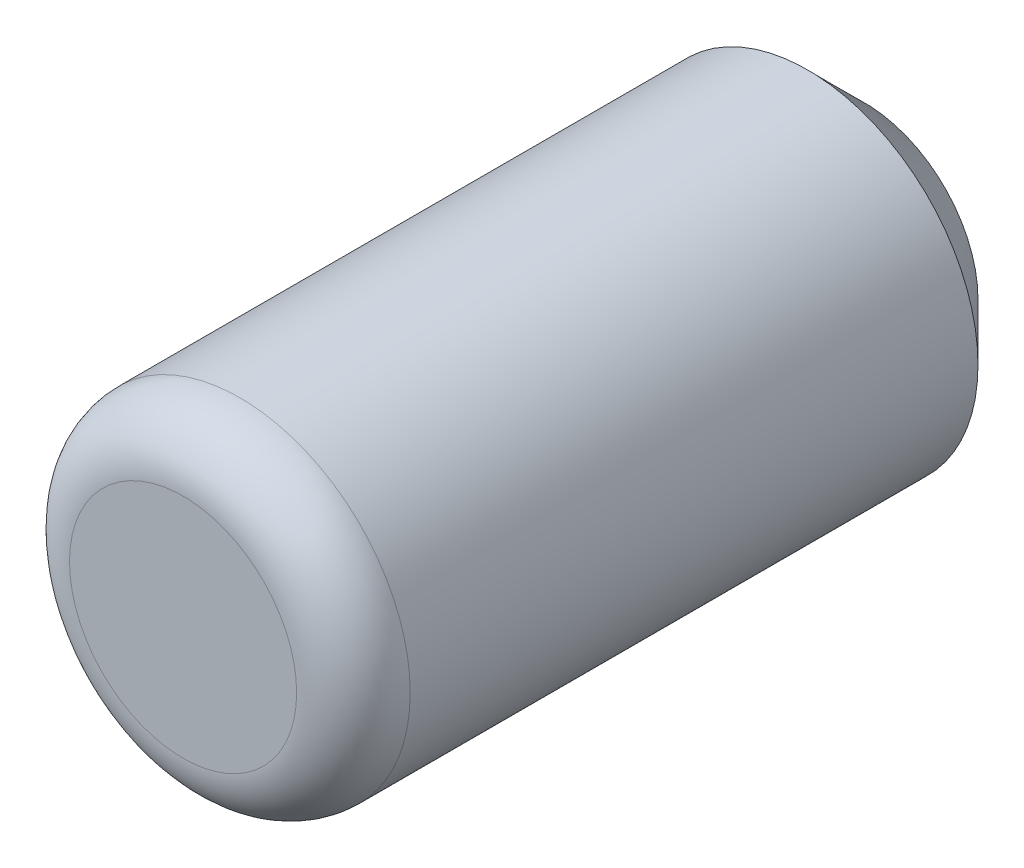
SolidWorks part; units mm, degrees
ref_plane "Front Plane" through (0, 0, 0) normal (0, 0, 1) x (1, 0, 0)
ref_plane "Top Plane" through (0, 0, 0) normal (0, 1, 0) x (1, 0, 0)
ref_plane "Right Plane" through (0, 0, 0) normal (1, 0, 0) x (0, 0, -1)
sketch "Sketch1" plane through (0, 0, 0) normal (0, 0, 1) x (1, 0, 0)
  circle A0 centre (0, 0) radius 2.3813
  dimension "D1" = 4.7625
extrude "Extrude1" add sketch "Sketch1" along normal mid plane 9.525
fillet "Fillet1" radius 0.7937 1 edges at (2.3813, 0, 4.7625)
chamfer "Chamfer1" distance 0.7937 angle 45 1 edges at (2.3813, 0, -4.7625)
